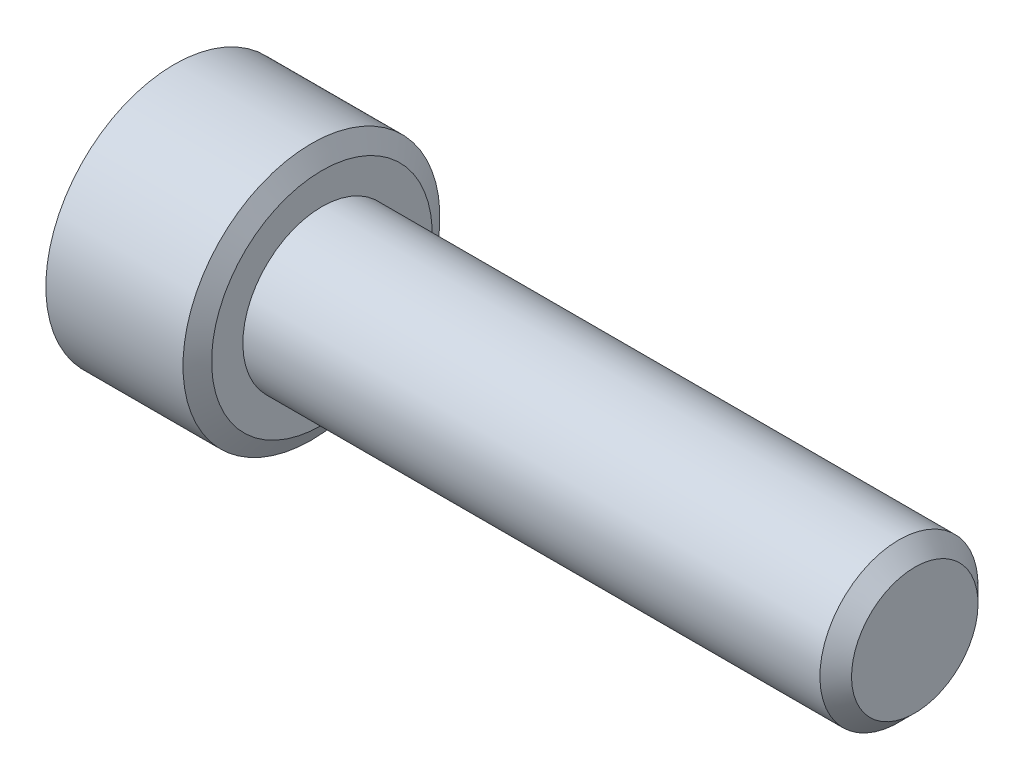
SolidWorks part; units mm, degrees
ref_plane "Front Plane" through (0, 0, 0) normal (0, 0, 1) x (1, 0, 0)
ref_plane "Top Plane" through (0, 0, 0) normal (0, 1, 0) x (1, 0, 0)
ref_plane "Right Plane" through (0, 0, 0) normal (1, 0, 0) x (0, 0, -1)
sketch "Sketch1" plane through (0, 0, 0) normal (0, 0, 1) x (1, 0, 0)
  line L0 (0, 0) -> (0, 5.582)
  line L1 (0, 5.582) -> (0.53, 6.5)
  line L2 (0.53, 6.5) -> (7.47, 6.5)
  line L3 (7.47, 6.5) -> (8, 5.582)
  line L4 (8, 5.582) -> (8, 4)
  line L5 (8, 4) -> (38, 4)
  line L6 (38, 4) -> (38, 0)
  line L7 (38, 0) -> (0, 0) construction
  line L8 (0, 0) -> (38, 0)
  point P4 (6.9451, 8.6992)
  point P10 (7.3163, 8.7578)
  point P11 (8, 7.605)
  point P12 (7.9806, 6.335)
  point P13 (8, 6.8821)
  dimension "D1" = 30
  dimension "D2" = 8
  dimension "D3" = 30
  dimension "D4" = 30
  dimension "D5" = 6.5
  dimension "D6" = 0.53
  dimension "D7" = 0.53
  dimension "D8" = 4
revolve "Revolve1" add sketch "Sketch1" angle 360 about L7
chamfer "Chamfer1" distance 0.8 angle 45 1 edges at (38, 4, 0)
sketch "Sketch2" plane through (0, 0, 0) normal (-1, 0, 0) x (0, 0, 1)
  line L1 (3.7528, 0) -> (1.8764, 3.25)
  line L2 (1.8764, 3.25) -> (-1.8764, 3.25)
  line L3 (-1.8764, 3.25) -> (-3.7528, 0)
  line L4 (-3.7528, 0) -> (-1.8764, -3.25)
  line L5 (-1.8764, -3.25) -> (1.8764, -3.25)
  line L6 (1.8764, -3.25) -> (3.7528, 0)
  circle A0 centre (0, 0) radius 3.25 construction
  point P1 (0, 0)
  point P10 (0, 0)
  point P11 (0, 0)
  point P12 (0, 0)
  point P13 (0, 0)
  point P14 (0, 0)
  dimension "D1" = 6.5
extrude "Cut-Extrude1" cut sketch "Sketch2" against normal blind 6
sketch "Sketch4" plane through (0, 0, 0) normal (0, 0, 1) x (1, 0, 0)
  line L0 (0, 0) -> (10.9165, 0) construction
  line L1 (0, 0) -> (0, 4)
  line L2 (0, 5.582) -> (0, -5.582) construction
  line L3 (0, 4) -> (2.3094, 0)
  line L4 (2.3094, 0) -> (0, 0)
  line L5 (6, 0) -> (6, 4)
  line L6 (6, 4) -> (8.3094, 0)
  line L7 (8.3094, 0) -> (6, 0)
  point P9 (6, 0)
  dimension "D1" = 30
  dimension "D2" = 4
  dimension "D3" = 30
  dimension "D4" = 4
revolve "Cut-Revolve1" cut sketch "Sketch4" angle 360 about L0
